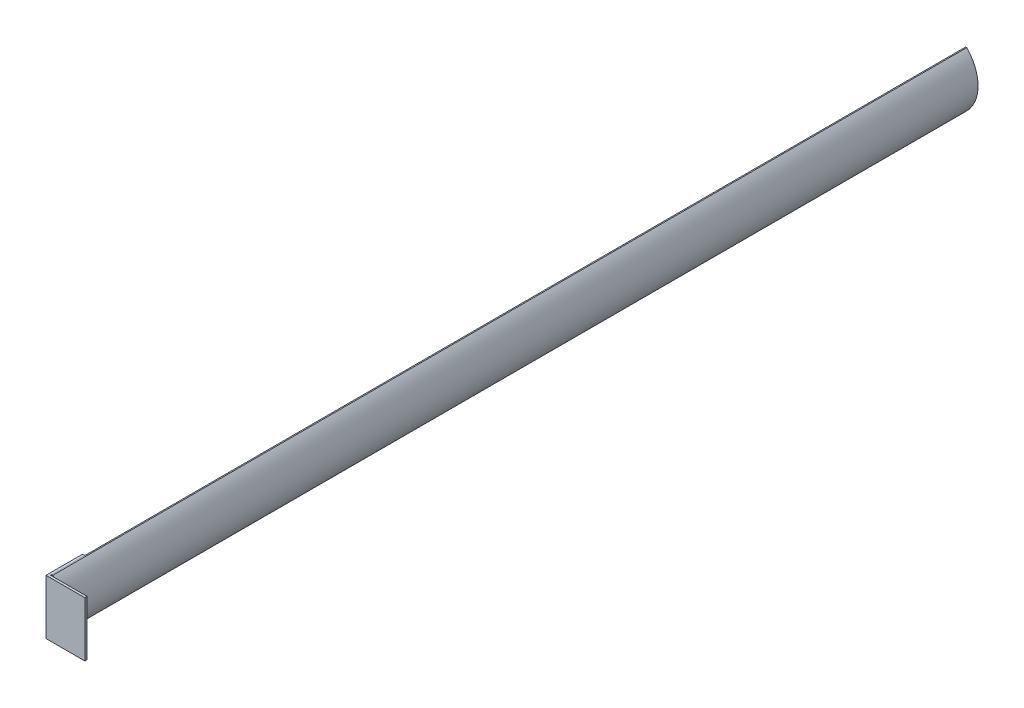
SolidWorks part; units mm, degrees
ref_plane "Alzado" through (0, 0, 0) normal (0, 0, 1) x (1, 0, 0)
ref_plane "Planta" through (0, 0, 0) normal (0, 1, 0) x (1, 0, 0)
ref_plane "Vista lateral" through (0, 0, 0) normal (1, 0, 0) x (0, 0, -1)
sketch "Croquis1" plane through (0, 0, 0) normal (0, 0, 1) x (1, 0, 0)
  line L0 (-0.5, -12) -> (4.5, -12) construction
  line L1 (0, 0) -> (-0.5, 0)
  line L2 (0, 0) -> (0, -24) construction
  line L3 (0, -24) -> (-0.5, -24)
  line L4 (-0.5, 0) -> (-0.5, -24) construction
  line L5 (4.5, -12) -> (5, -12) construction
  arc A0 (-0.5, 0) -> (-0.5, -24) centre (-12.5, -12) cw
  arc A1 (0, -24) -> (0, 0) centre (-12, -12) ccw
  dimension "D3" = 5
  dimension "D1" = 24
  dimension "D2" = 0.5
  dimension "D4" = 0.5
extrude "Saliente-Extruir1" add sketch "Croquis1" along normal blind 400
sketch "Croquis2" plane through (0, 0, 0) normal (0, 1, 0) x (1, 0, 0)
  line L0 (0, -400) -> (-0.5, -400) construction
  line L1 (-1.5, -385.5) -> (-0.5, -385.5)
  line L4 (-0.5, -385.5) -> (-0.5, -400.5)
  line L10 (-1.5, -385.5) -> (-1.5, -401.5)
  line L12 (-0.5, -400) -> (-0.5, 0) construction
  line L13 (-0.5, -400.5) -> (15.5, -400.5)
  line L14 (15.5, -400.5) -> (15.5, -401.5)
  line L17 (15.5, -401.5) -> (-1.5, -401.5)
  dimension "D1" = 1
  dimension "D2" = 1
  dimension "D3" = 14.5
  dimension "D4" = 16
  dimension "D6" = 17
extrude "Saliente-Extruir6" add sketch "Croquis2" against normal up to surface (24 mm away) separate body up to face at (-0.25, -24, 200)
